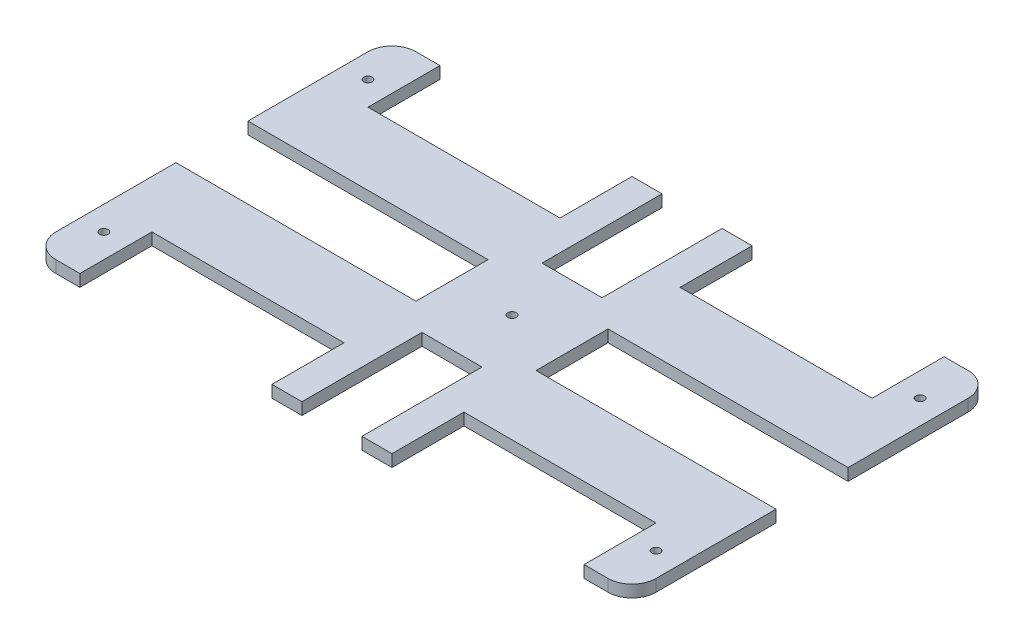
SolidWorks part; units mm, degrees
ref_plane "前视基准面" through (0, 0, 0) normal (0, 0, 1) x (1, 0, 0)
ref_plane "上视基准面" through (0, 0, 0) normal (0, 1, 0) x (1, 0, 0)
ref_plane "右视基准面" through (0, 0, 0) normal (1, 0, 0) x (0, 0, -1)
other "Configuration Table"
sketch "草图1" plane through (0, 0, 0) normal (0, 1, 0) x (1, 0, 0)
  line L1 (125, -75) -> (-125, -75)
  line L2 (125, -75) -> (125, 75)
  line L3 (125, 75) -> (-125, 75)
  line L4 (-125, -75) -> (-125, 75)
  line L5 (125, -75) -> (-125, 75) construction
  line L6 (125, 75) -> (-125, -75) construction
  point P0 (0, 0)
  dimension "D1" = 250
  dimension "D2" = 150
extrude "凸台-拉伸1" add sketch "草图1" along normal blind 5
fillet "圆角1" radius 10 4 edges at (-125, 2.5, -75) (125, 2.5, -75) (125, 2.5, 75) (-125, 2.5, 75)
sketch "草图2" plane through (0, 5, 0) normal (0, 1, 0) x (1, 0, 0)
  line L0 (-115, -75) -> (115, -75) construction
  line L1 (-125, 65) -> (-125, -65) construction
  circle A0 centre (-115, -55) radius 1.75
  point P2 (0, 0)
  point P7 (-112.0123, -51.0744)
  dimension "D1" = 3.5
  dimension "D2" = 20
  dimension "D3" = 10
extrude "切除-拉伸1" cut sketch "草图2" against normal through all both and the other way through all
mirror "镜向1" about plane through (0, 0, 0) normal (0, 0, 1) of "切除-拉伸1"
mirror "镜向2" about plane through (0, 0, 0) normal (1, 0, 0) of "镜向1", "切除-拉伸1"
sketch "草图4" plane through (0, 5, 0) normal (0, 1, 0) x (1, 0, 0)
  circle A0 centre (0, 0) radius 1.75
  dimension "D1" = 3.5
extrude "切除-拉伸2" cut sketch "草图4" against normal blind 5
sketch "草图5" plane through (0, 0, 0) normal (0, -1, 0) x (1, 0, 0)
  line L0 (0, 75) -> (0, -75) construction
  line L1 (-115, 75) -> (115, 75) construction
  line L2 (115, -75) -> (-115, -75) construction
  line L3 (-125, 0) -> (125, 0) construction
  line L4 (-125, -65) -> (-125, 65) construction
  line L5 (125, 65) -> (125, -65) construction
  line L7 (12.5, 25) -> (-12.5, 25)
  line L8 (12.5, 25) -> (12.5, 75)
  line L9 (12.5, 75) -> (-12.5, 75)
  line L10 (-12.5, 25) -> (-12.5, 75)
  line L11 (12.5, 25) -> (-12.5, 75) construction
  line L12 (12.5, 75) -> (-12.5, 25) construction
  point P12 (0, 50)
  dimension "D1" = 25
  dimension "D2" = 50
extrude "切除-拉伸3" cut sketch "草图5" against normal blind 5
sketch "草图7" plane through (0, 0, 0) normal (0, -1, 0) x (1, 0, 0)
  line L0 (0, -13.3899) -> (0, -88.3899) construction
  line L2 (115, -75) -> (-115, -75) construction
  line L3 (105, -45) -> (-105, -45)
  line L4 (105, -45) -> (105, -75)
  line L5 (105, -75) -> (-105, -75)
  line L6 (-105, -45) -> (-105, -75)
  line L7 (105, -45) -> (-105, -75) construction
  line L8 (105, -75) -> (-105, -45) construction
  line L9 (125, 65) -> (125, -65) construction
  point P1 (0, -60)
  dimension "D1" = 210
  dimension "D2" = 30
  dimension "D3" = 20
extrude "切除-拉伸4" cut sketch "草图7" against normal blind 5
mirror "镜向3" about plane through (0, 0, 0) normal (0, 0, 1) of "切除-拉伸4"
mirror "镜向4" about plane through (0, 0, 0) normal (0, 0, 1) of "切除-拉伸3"
sketch "草图8" plane through (0, 5, 0) normal (0, 1, 0) x (1, 0, 0)
  line L0 (-25, -45) -> (-12.5, -45)
  line L1 (-25, -45) -> (-25, -75)
  line L2 (-12.5, -45) -> (-12.5, -75)
  line L3 (-25, -75) -> (-12.5, -75)
  line L4 (-12.5, -45) -> (-105, -45) construction
  dimension "D1" = 30
  dimension "D2" = 12.5
extrude "凸台-拉伸2" add sketch "草图8" against normal blind 5
mirror "镜向5" about plane through (0, 0, 0) normal (1, 0, 0) of "凸台-拉伸2" second plane through (0, 0, 0) second plane normal (0, 0, 1)
sketch "草图9" plane through (0, 5, 0) normal (0, 1, 0) x (1, 0, 0)
  line L0 (-125, 0) -> (125, 0) construction
  line L1 (-125, 65) -> (-125, -65) construction
  line L2 (125, -65) -> (125, 65) construction
  line L4 (-25, -15) -> (-125, -15)
  line L5 (-25, -15) -> (-25, 15)
  line L6 (-25, 15) -> (-125, 15)
  line L7 (-125, -15) -> (-125, 15)
  line L8 (-25, -15) -> (-125, 15) construction
  line L9 (-25, 15) -> (-125, -15) construction
  point P6 (-75, 0)
  dimension "D1" = 100
  dimension "D2" = 30
extrude "切除-拉伸5" cut sketch "草图9" against normal blind 5
mirror "镜向6" about plane through (0, 0, 0) normal (1, 0, 0) of "切除-拉伸5"
